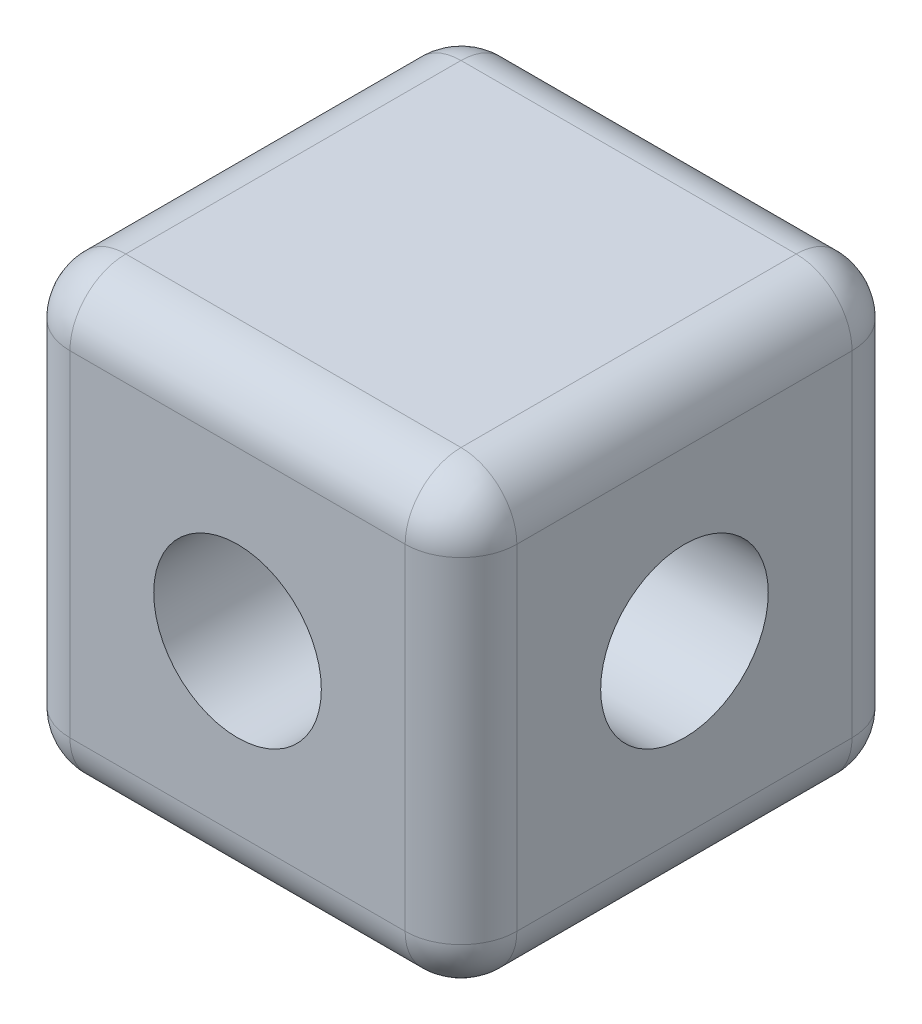
SolidWorks part; units mm, degrees
ref_plane "前视基准面" through (0, 0, 0) normal (0, 0, 1) x (1, 0, 0)
ref_plane "上视基准面" through (0, 0, 0) normal (0, 1, 0) x (1, 0, 0)
ref_plane "右视基准面" through (0, 0, 0) normal (1, 0, 0) x (0, 0, -1)
sketch "草图1" plane through (0, 0, 0) normal (0, 1, 0) x (1, 0, 0)
  line L0 (-2, 2) -> (2, 2)
  line L2 (2, 2) -> (2, -2)
  line L3 (2, -2) -> (-2, -2)
  line L4 (-2, -2) -> (-2, 2)
extrude "凸台-拉伸1" add sketch "草图1" along normal blind 4
fillet "圆角1" radius 0.5 1 edges at (0, 4, 2)
fillet "圆角2" radius 0.5 3 edges at (2, 4, -0.25) (2, 1.75, 2) (2, 3.8536, 1.8536)
fillet "圆角3" radius 0.5 3 edges at (-2, 4, -0.25) (-2, 1.75, 2) (-2, 3.8536, 1.8536)
fillet "圆角4" radius 0.5 5 edges at (2, 1.75, -2) (0, 4, -2) (1.8536, 3.8536, -2) (-2, 1.75, -2) (-1.8536, 3.8536, -2)
fillet "圆角5" radius 0.5 8 edges at (2, 0, 0) (1.8536, 0, 1.8536) (0, 0, 2) (-1.8536, 0, 1.8536) (0, 0, -2) (-2, 0, 0) (-1.8536, 0, -1.8536) (1.8536, 0, -1.8536)
sketch "草图2" plane through (0, 0, 2) normal (0, 0, 1) x (1, 0, 0)
  circle A0 centre (0, 2) radius 0.75
extrude "切除-拉伸1" cut sketch "草图2" against normal up to next
sketch "草图3" plane through (-2, 0, 0) normal (-1, 0, 0) x (0, 0, 1)
  circle A0 centre (0, 2) radius 0.75
extrude "切除-拉伸2" cut sketch "草图3" against normal blind 4
